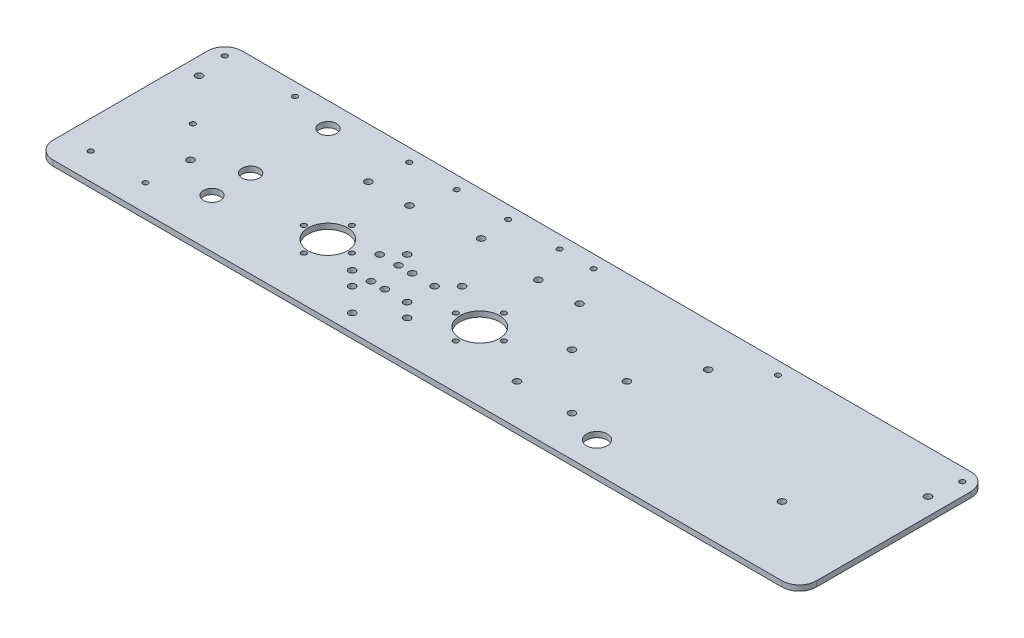
SolidWorks part; units mm, degrees
ref_plane "Front" through (0, 0, 0) normal (0, 0, 1) x (1, 0, 0)
ref_plane "Top" through (0, 0, 0) normal (0, 1, 0) x (1, 0, 0)
ref_plane "Right" through (0, 0, 0) normal (1, 0, 0) x (0, 0, -1)
sketch "Sketch1" plane through (0, 0, 0) normal (0, 1, 0) x (1, 0, 0)
  line L0 (-26.7996, 0) -> (-26.7996, 40)
  line L1 (-26.7996, 0) -> (417.7004, 0)
  line L2 (-26.7996, 0) -> (-26.7996, 110)
  line L3 (-26.7996, 110) -> (417.7004, 110)
  line L4 (417.7004, 0) -> (417.7004, 110)
  line L5 (-26.7996, 40) -> (23.2004, 40)
  line L6 (417.7004, 0) -> (417.7004, 40)
  line L7 (417.7004, 40) -> (367.7004, 40)
  line L8 (23.2004, 40) -> (103.2004, 40)
  line L9 (367.7004, 40) -> (191.7004, 40)
  line L10 (-26.7996, 110) -> (-26.7996, 85)
  line L11 (-26.7996, 85) -> (417.7004, 85)
  line L12 (-26.7996, 85) -> (-16.7996, 85)
  line L13 (417.7004, 85) -> (407.7004, 85)
  line L14 (103.2004, 40) -> (191.7004, 40)
  line L15 (147.4504, 40) -> (147.4504, 85)
  line L16 (279.7004, 40) -> (279.7004, 85)
  line L17 (147.4504, 40) -> (147.4504, 10)
  line L18 (-26.7996, 110) -> (-26.7996, 102.5)
  line L19 (-26.7996, 102.5) -> (417.7004, 102.5)
  line L20 (-26.7996, 102.5) -> (-19.2996, 102.5)
  line L21 (417.7004, 102.5) -> (410.2004, 102.5)
  line L22 (195.4504, 102.5) -> (410.2004, 102.5)
  line L23 (-19.2996, 102.5) -> (195.4504, 102.5)
  line L24 (417.7004, 0) -> (417.7004, 17.2282)
  line L25 (417.7004, 17.2282) -> (282.7004, 17.2282)
  circle A10 centre (367.7004, 40) radius 2
  circle A11 centre (23.2004, 40) radius 2
  circle A12 centre (103.2004, 40) radius 11.5
  circle A13 centre (103.2004, 40) radius 14
  circle A15 centre (103.2004, 54) radius 1.5
  circle A16 centre (89.2004, 40) radius 1.5
  circle A17 centre (103.2004, 26) radius 1.5
  circle A18 centre (117.2004, 40) radius 1.5
  circle A19 centre (191.7004, 40) radius 11.5
  circle A20 centre (191.7004, 40) radius 14
  circle A21 centre (191.7004, 26) radius 1.5
  circle A22 centre (205.7004, 40) radius 1.5
  circle A23 centre (191.7004, 54) radius 1.5
  circle A24 centre (177.7004, 40) radius 1.5
  circle A25 centre (-16.7996, 85) radius 2
  circle A26 centre (407.7004, 85) radius 2
  circle A27 centre (147.4504, 85) radius 2
  circle A28 centre (279.7004, 85) radius 2
  circle A29 centre (147.4504, 10) radius 2
  circle A30 centre (195.4504, 102.5) radius 1.5
  circle A31 centre (-19.2996, 102.5) radius 1.5
  circle A32 centre (410.2004, 102.5) radius 1.5
  circle A33 centre (302.8254, 102.5) radius 1.5
  circle A34 centre (88.0754, 102.5) radius 1.5
  circle A35 centre (282.7004, 17.2282) radius 6
  dimension "D3" = 40
  dimension "D7" = 80
  dimension "D8" = 176
  dimension "D9" = 25
  dimension "D11" = 10
  dimension "D12" = 30
  dimension "D13" = 7.5
  dimension "D14" = 7.5
  dimension "D16" = 17.2282
  dimension "D1" = 110
  dimension "D2" = 444.5
  dimension "D4" = 50
  dimension "D5" = 40
  dimension "D6" = 50
  dimension "D10" = 10
  dimension "D15" = 7.5
  dimension "D17" = 135
extrude "Boss-Extrude1" add sketch "Sketch1" along normal blind 3.175
fillet "Fillet1" radius 10 4 edges at (417.7004, 1.5875, -110) (417.7004, 1.5875, 0) (-26.7996, 1.5875, 0) (-26.7996, 1.5875, -110)
sketch "Sketch2" plane through (0, 3.175, 0) normal (0, 1, 0) x (1, 0, 0)
  line L0 (-26.7996, 55.4056) -> (36.2004, 55.4056)
  line L1 (-26.7996, 10) -> (-26.7996, 100) construction
  line L2 (36.2004, 55.4056) -> (76.2004, 55.4056)
  line L3 (-16.7996, 110) -> (407.7004, 110) construction
  line L4 (36.2004, 55.4056) -> (36.2004, 23.4056)
  line L5 (36.2004, 23.4056) -> (68.2004, 23.4056)
  line L6 (76.2004, 55.4056) -> (165.9504, 55.4056)
  line L7 (165.9504, 55.4056) -> (133.9504, 55.4056)
  line L8 (133.9504, 55.4056) -> (133.9504, 23.4056)
  line L9 (133.9504, 23.4056) -> (165.9504, 23.4056)
  line L10 (133.9504, 23.4056) -> (125.9504, 23.4056)
  line L11 (125.9504, 23.4056) -> (125.9504, 55.4056)
  line L12 (165.9504, 55.4056) -> (157.9504, 55.4056)
  line L13 (157.9504, 55.4056) -> (157.9504, 23.4056)
  line L14 (157.9504, 23.4056) -> (157.9504, 31.4056)
  line L15 (157.9504, 55.4056) -> (157.9504, 47.4056)
  line L16 (157.9504, 47.4056) -> (133.9504, 47.4056)
  circle A4 centre (133.9504, 55.4056) radius 2
  circle A5 centre (165.9504, 55.4056) radius 2
  circle A9 centre (133.9504, 23.4056) radius 2
  circle A10 centre (165.9504, 23.4056) radius 2
  circle A11 centre (157.9504, 31.4056) radius 2
  circle A12 centre (125.9504, 31.4056) radius 2
  circle A13 centre (125.9504, 47.4056) radius 2
  circle A14 centre (157.9504, 47.4056) radius 2
  dimension "D5" = 89.75
  dimension "D6" = 32
  dimension "D7" = 8
  dimension "D10" = 8
  dimension "D1" = 63
  dimension "D2" = 40
  dimension "D3" = 54.5944
  dimension "D4" = 32
  dimension "D8" = 8
  dimension "D9" = 8
extrude "Cut-Extrude1" cut sketch "Sketch2" against normal blind 10
sketch "Sketch3" plane through (0, 0, 0) normal (0, -1, 0) x (1, 0, 0)
  line L0 (133.9504, -55.4056) -> (133.9504, -47.4056)
  line L1 (133.9504, -47.4056) -> (136.9504, -47.4056)
  line L2 (136.9504, -47.4056) -> (144.9504, -47.4056)
  line L3 (136.9504, -47.4056) -> (136.9504, -31.4056)
  line L4 (136.9504, -31.4056) -> (144.9504, -31.4056)
  line L5 (165.9504, -55.4056) -> (229.9504, -55.4056)
  line L6 (229.9504, -55.4056) -> (261.9504, -55.4056)
  line L7 (261.9504, -55.4056) -> (261.9504, -23.4056)
  line L8 (261.9504, -23.4056) -> (229.9504, -23.4056)
  circle A0 centre (144.9504, -47.4056) radius 2
  circle A1 centre (136.9504, -47.4056) radius 2
  circle A2 centre (144.9504, -31.4056) radius 2
  circle A3 centre (136.9504, -31.4056) radius 2
  circle A4 centre (261.9504, -55.4056) radius 2
  circle A5 centre (229.9504, -55.4056) radius 2
  circle A6 centre (261.9504, -23.4056) radius 2
  circle A7 centre (229.9504, -23.4056) radius 2
  dimension "D3" = 8
  dimension "D5" = 64
  dimension "D7" = 32
  dimension "D1" = 3
  dimension "D2" = 8
  dimension "D4" = 16
  dimension "D6" = 32
extrude "Cut-Extrude2" cut sketch "Sketch3" against normal blind 10
sketch "Sketch4" plane through (0, 3.175, 0) normal (0, 1, 0) x (1, 0, 0)
  circle A0 centre (21.5907, 102.5) radius 1.5
  circle A1 centre (5.6648, 58.9528) radius 1.5
  circle A2 centre (-10.261, 15.4056) radius 1.5
  circle A3 centre (47.3504, 50.9056) radius 2
  circle A4 centre (115.6708, 102.5) radius 1.5
  circle A5 centre (145.6708, 102.5) radius 1.5
  circle A6 centre (175.6708, 102.5) radius 1.5
  circle A7 centre (47.3504, 95.9056) radius 2
  circle A8 centre (21.5907, 15.4056) radius 1.5
  circle A9 centre (47.3504, 28.4056) radius 2
  circle A10 centre (208.9504, 80.8056) radius 2
  circle A11 centre (184.9504, 80.8056) radius 2
  circle A12 centre (109.9504, 80.8056) radius 2
  circle A13 centre (85.9504, 80.8056) radius 2
extrude "Cut-Extrude3" cut sketch "Sketch4" against normal blind 6.35 contours A2
sketch "Sketch5" plane through (0, 3.175, 0) normal (0, 1, 0) x (1, 0, 0)
  circle A0 centre (47.3504, 95.9056) radius 5
  circle A1 centre (47.3504, 50.9056) radius 5
  circle A2 centre (47.3504, 28.4056) radius 5
extrude "Cut-Extrude4" cut sketch "Sketch5" against normal blind 3.175
